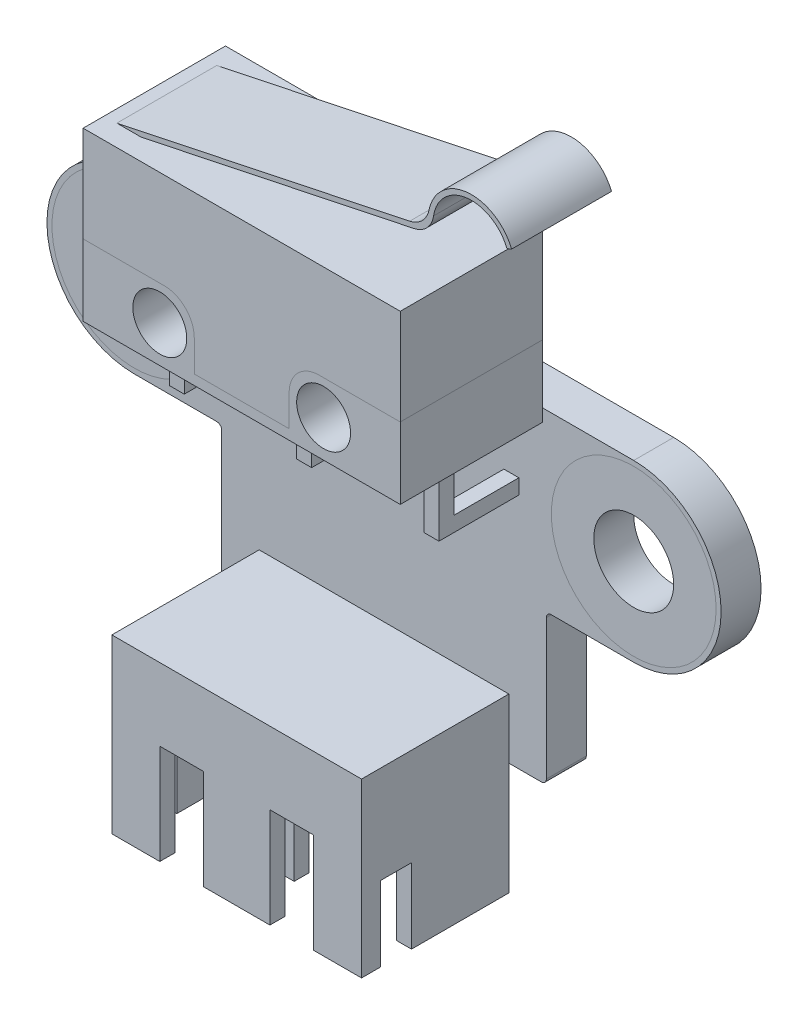
SolidWorks part; units mm, degrees
ref_plane "Přední rovina" through (0, 0, 0) normal (0, 0, 1) x (1, 0, 0)
ref_plane "Horní rovina" through (0, 0, 0) normal (0, 1, 0) x (1, 0, 0)
ref_plane "Pravá rovina" through (0, 0, 0) normal (1, 0, 0) x (0, 0, -1)
sketch "Skica1" plane through (0, 0, 0) normal (0, 0, 1) x (1, 0, 0)
  line L0 (0, 0) -> (20, 0) construction
  line L1 (0, 3.5) -> (20, 3.5)
  line L2 (0, -3.5) -> (3.5, -3.5)
  line L3 (3.5, -3.5) -> (3.5, -9.5)
  line L4 (3.5, -9.5) -> (16.5, -9.5)
  line L5 (16.5, -9.5) -> (16.5, -3.5)
  line L6 (16.5, -3.5) -> (20, -3.5)
  arc A0 (0, 3.5) -> (0, -3.5) centre (0, 0) ccw
  arc A1 (20, -3.5) -> (20, 3.5) centre (20, 0) ccw
  circle A2 centre (0, 0) radius 1.6
  circle A3 centre (20, 0) radius 1.6
  point P2 (0, 0)
  dimension "D1" = 27
  dimension "D5" = 3.2
  dimension "D6" = 3.2
  dimension "D2" = 13
  dimension "D3" = 13
  dimension "D4" = 20
extrude "Přidat vysunutím1" add sketch "Skica1" along normal blind 1.6
sketch "Skica2" plane through (0, 0, 1.6) normal (0, 0, 1) x (1, 0, 0)
  line L0 (20, 3.5) -> (0, 3.5) construction
  line L1 (3.65, 9.7) -> (16.35, 9.7)
  line L2 (3.65, 9.7) -> (3.65, 3)
  line L3 (3.65, 3) -> (16.35, 3)
  line L4 (16.35, 9.7) -> (16.35, 3)
  line L5 (3.65, 9.7) -> (16.35, 3) construction
  line L6 (3.65, 3) -> (16.35, 9.7) construction
  line L7 (10, 6.35) -> (10, -9.5) construction
  line L8 (3.5, -9.5) -> (16.5, -9.5) construction
  point P0 (10, 6.35)
  dimension "D1" = 6.2
  dimension "D2" = 12.7
  dimension "D3" = 6.7
extrude "Přidat vysunutím2" add sketch "Skica2" along normal blind 5.7
sketch "Skica3" plane through (0, 0, 1.6) normal (0, 0, 1) x (1, 0, 0)
  line L0 (3.5, -9.5) -> (16.5, -9.5) construction
  line L1 (5, -7.1) -> (15, -7.1)
  line L2 (5, -7.1) -> (5, -14)
  line L3 (5, -14) -> (15, -14)
  line L4 (15, -7.1) -> (15, -14)
  line L5 (5, -7.1) -> (15, -14) construction
  line L6 (5, -14) -> (15, -7.1) construction
  line L7 (10, -9.5) -> (10, -10.55) construction
  point P0 (10, -10.55)
  dimension "D1" = 10
  dimension "D2" = 6.9
  dimension "D3" = 4.5
extrude "Přidat vysunutím3" add sketch "Skica3" along normal blind 5.9
sketch "Skica4" plane through (0, -14, 0) normal (0, -1, 0) x (1, 0, 0)
  line L0 (5, 7.5) -> (15, 7.5) construction
  line L1 (5.6, 6.9) -> (14.4, 6.9)
  line L2 (5.6, 6.9) -> (5.6, 2.2)
  line L3 (5.6, 2.2) -> (14.4, 2.2)
  line L4 (14.4, 6.9) -> (14.4, 2.2)
  line L5 (15, 7.5) -> (15, 1.6) construction
  line L6 (5, 7.5) -> (5, 1.6) construction
  line L7 (5, 1.6) -> (15, 1.6) construction
  line L8 (9.7, 5.5) -> (10.3, 5.5)
  line L9 (7.16, 5.5) -> (7.76, 5.5)
  line L10 (7.16, 5.5) -> (7.16, 4.9)
  line L11 (7.16, 4.9) -> (7.76, 4.9)
  line L12 (7.76, 5.5) -> (7.76, 4.9)
  line L13 (7.16, 5.5) -> (7.76, 4.9) construction
  line L14 (7.16, 4.9) -> (7.76, 5.5) construction
  line L15 (9.7, 4.9) -> (10.3, 4.9)
  line L16 (10.3, 5.5) -> (10.3, 4.9)
  line L17 (9.7, 5.5) -> (9.7, 4.9)
  line L18 (12.24, 5.5) -> (12.84, 5.5)
  line L19 (12.24, 4.9) -> (12.84, 4.9)
  line L20 (12.84, 5.5) -> (12.84, 4.9)
  line L21 (12.24, 5.5) -> (12.24, 4.9)
  line L22 (10, 4.9) -> (10, 2.2) construction
  point P12 (7.46, 5.2)
  dimension "D1" = 0.6
  dimension "D2" = 0.6
  dimension "D3" = 0.6
  dimension "D4" = 0.6
  dimension "D5" = 0.6
  dimension "D7" = 2.54
  dimension "D8" = 3.9
  dimension "D6" = 3
extrude "Odebrat vysunutím1" cut sketch "Skica4" against normal blind 5.4
sketch "Skica5" plane through (15, 0, 0) normal (1, 0, 0) x (0, 0, -1)
  line L0 (-7.5, -14) -> (-7.5, -7.1) construction
  line L1 (-5.5, -14) -> (-6.75, -14)
  line L2 (-5.5, -14) -> (-5.5, -11)
  line L3 (-5.5, -11) -> (-6.75, -11)
  line L4 (-6.75, -14) -> (-6.75, -11)
  dimension "D1" = 0.75
  dimension "D2" = 3
extrude "Odebrat vysunutím2" cut sketch "Skica5" against normal blind 11.4
sketch "Skica6" plane through (0, 0, 7.5) normal (0, 0, 1) x (1, 0, 0)
  line L0 (5, -14) -> (15, -14) construction
  line L1 (13.08, -14) -> (11.33, -14)
  line L2 (13.08, -14) -> (13.08, -10)
  line L3 (13.08, -10) -> (11.33, -10)
  line L4 (11.33, -14) -> (11.33, -10)
  line L5 (15, -14) -> (15, -7.1) construction
  line L6 (10, -14) -> (10, -7.1) construction
  line L8 (15, -7.1) -> (5, -7.1) construction
  line L9 (8.67, -14) -> (8.67, -10)
  line L10 (6.92, -10) -> (8.67, -10)
  line L11 (6.92, -14) -> (6.92, -10)
  line L12 (6.92, -14) -> (8.67, -14)
  dimension "D1" = 1.92
  dimension "D2" = 1.75
  dimension "D3" = 4
extrude "Odebrat vysunutím3" cut sketch "Skica6" against normal blind 1
sketch "Skica7" plane through (0, 0, 1.6) normal (0, 0, 1) x (1, 0, 0)
  circle A0 centre (0, 0) radius 3.3
  arc A1 (0, 3.5) -> (0, -3.5) centre (0, 0) ccw construction
  circle A2 centre (20, 0) radius 3.3
  arc A3 (20, -3.5) -> (20, 3.5) centre (20, 0) ccw construction
  dimension "D1" = 0.2
  dimension "D2" = 0.2
split line "Rozdělovací křivka1"
fillet "Zaoblit1" radius 0.2 4 edges at (3.5, -9.5, 0.8) (16.5, -9.5, 0.8) (16.5, -3.5, 0.8) (3.5, -3.5, 0.8)
sketch "Skica8" plane through (0, -2.8, 7.3) normal (0, 0, -1) x (1, 0, 0)
  line L1 (6.72, -7.28) -> (13.28, -7.28) construction
  line L2 (13.28, -7.28) -> (10, -12.5) construction
  line L3 (16.35, -12.5) -> (3.65, -12.5) construction
  line L4 (10, -12.5) -> (6.72, -7.28) construction
  line L5 (3.65, -5.8) -> (16.35, -5.8) construction
  circle A0 centre (6.72, -7.28) radius 1.08
  circle A1 centre (13.28, -7.28) radius 1.08
  dimension "D1" = 4.4
  dimension "D2" = 8.72
  dimension "D3" = 1.48
extrude "Odebrat vysunutím4" cut sketch "Skica8" along normal up to surface (5.7 mm away) up to face at (3.3, 0, 1.6)
sketch "Skica9" plane through (0, 0, 7.3) normal (0, 0, 1) x (1, 0, 0)
  line L0 (3.65, 5.86) -> (6.9, 5.86)
  line L1 (3.65, 9.7) -> (3.65, 3) construction
  line L2 (8.1, 4.66) -> (8.1, 3.4)
  line L3 (8.1, 3.4) -> (11.9, 3.4)
  line L4 (11.9, 3.4) -> (11.9, 4.66)
  line L5 (13.1, 5.86) -> (16.35, 5.86)
  line L6 (16.35, 3) -> (16.35, 9.7) construction
  line L7 (3.65, 3) -> (16.35, 3) construction
  circle A1 centre (6.72, 4.48) radius 1.08 construction
  circle A3 centre (13.28, 4.48) radius 1.08 construction
  arc A4 (11.9, 4.66) -> (13.1, 5.86) centre (13.1, 4.66) cw
  arc A5 (8.1, 4.66) -> (6.9, 5.86) centre (6.9, 4.66) ccw
  dimension "D5" = 1.2
  dimension "D1" = 0.3
  dimension "D2" = 0.3
  dimension "D3" = 0.3
  dimension "D4" = 0.4
ref_plane "Rovina1" through (0, 0, 4.45) normal (0, 0, 1) x (1, 0, 0)
split line "Rozdělovací křivka2"
sketch "Skica11" plane through (16.35, 0, 0) normal (1, 0, 0) x (0, 0, -1)
  line L0 (-7.3, 5.86) -> (-1.6, 5.86)
  line L1 (-1.6, 3.5) -> (-1.6, 9.7) construction
split line "Rozdělovací křivka3"
sketch "Skica12" plane through (0, 0, 1.6) normal (0, 0, -1) x (-1, 0, 0)
  line L0 (-6.9, 5.86) -> (-3.65, 5.86) construction
  line L1 (-11.9, 4.66) -> (-11.9, 3.4) construction
  line L2 (-8.1, 3.4) -> (-8.1, 4.66) construction
  line L3 (-11.9, 3.4) -> (-8.1, 3.4) construction
  line L4 (-16.35, 5.86) -> (-13.1, 5.86) construction
  line L5 (-6.9, 5.86) -> (-3.65, 5.86)
  line L6 (-11.9, 4.66) -> (-11.9, 3.4)
  line L7 (-8.1, 3.4) -> (-8.1, 4.66)
  line L8 (-11.9, 3.4) -> (-8.1, 3.4)
  line L9 (-16.35, 5.86) -> (-13.1, 5.86)
  arc A0 (-6.9, 5.86) -> (-8.1, 4.66) centre (-6.9, 4.66) ccw construction
  arc A1 (-11.9, 4.66) -> (-13.1, 5.86) centre (-13.1, 4.66) ccw construction
  arc A2 (-6.9, 5.86) -> (-8.1, 4.66) centre (-6.9, 4.66) ccw
  arc A3 (-11.9, 4.66) -> (-13.1, 5.86) centre (-13.1, 4.66) ccw
split line "Rozdělovací křivka4"
ref_plane "Rovina2" through (0, 0, 4.45) normal (0, 0, 1) x (1, 0, 0)
sketch "Skica14" plane through (3.65, 0, 0) normal (-1, 0, 0) x (0, 0, 1)
  line L0 (1.6, 5.86) -> (7.3, 5.86)
split line "Rozdělovací křivka5"
sketch "Skica15" plane through (0, 0, 4.45) normal (0, 0, 1) x (1, 0, 0)
  line L0 (4.15, 9.7) -> (15.8776, 12.1628)
  line L1 (16.35, 9.7) -> (3.65, 9.7) construction
  line L2 (3.65, 9.7) -> (3.65, 5.86) construction
  line L3 (4.15, 9.7) -> (5.1231, 9.7)
  line L4 (5.1231, 9.7) -> (16.0506, 11.9948)
  line L5 (16.35, 9.7) -> (16.35, 16.7874) construction
  line L6 (19.7738, 13.1612) -> (19.9595, 13.2357)
  line L7 (16.35, 5.86) -> (16.35, 9.7) construction
  circle A0 centre (4.15, 9.7) radius 16.2 construction
  arc A1 (19.9595, 13.2357) -> (16.6515, 12.9398) centre (18.35, 12.59) ccw
  arc A2 (19.7738, 13.1612) -> (16.8335, 12.8221) centre (18.35, 12.59) ccw
  arc A3 (16.8335, 12.8221) -> (16.0506, 11.9948) centre (15.845, 12.9735) cw
  arc A4 (16.6515, 12.9398) -> (15.8776, 12.1628) centre (15.672, 13.1415) cw
  dimension "D4" = 32.4
  dimension "D5" = 0.2
  dimension "D6" = 0.2
  dimension "1" = 1
  dimension "D1" = 0.5
  dimension "D2" = 0.2
  dimension "D3" = 11.86
  dimension "D7" = 2
  dimension "D8" = 2.89
  dimension "D9" = 190
extrude "Přidat vysunutím4" add sketch "Skica15" along normal mid plane 4 contours L0 A4 A1 L6 A2 A3 L4 L3
ref_plane "Rovina3" through (0, 0, 4.8) normal (0, 0, 1) x (1, 0, 0)
sketch "Skica16" plane through (0, 0, 4.8) normal (0, 0, 1) x (1, 0, 0)
  line L0 (3.65, 3) -> (16.35, 3) construction
  line L1 (5.2, 3) -> (4.6, 3)
  line L2 (5.2, 3) -> (5.2, 0)
  line L3 (5.2, 0) -> (4.6, 0)
  line L4 (4.6, 3) -> (4.6, 0)
  line L5 (10, 3) -> (10, 9.7) construction
  line L6 (9.7, 3) -> (10.3, 3)
  line L7 (9.7, 3) -> (9.7, 0)
  line L8 (9.7, 0) -> (10.3, 0)
  line L9 (10.3, 3) -> (10.3, 0)
  line L10 (14.8, 3) -> (15.4, 3)
  line L11 (14.8, 3) -> (14.8, 0)
  line L12 (14.8, 0) -> (15.4, 0)
  line L13 (15.4, 3) -> (15.4, 0)
  line L14 (16.35, 9.7) -> (3.65, 9.7) construction
  point P14 (4.9, 0)
  point P15 (10, 0)
  point P16 (15.1, 0)
  dimension "D1" = 3
  dimension "D2" = 5.1
  dimension "D3" = 5.1
  dimension "D4" = 0.6
extrude "Přidat vysunutím5" add sketch "Skica16" against normal up to surface (3.2 mm away) up to face at (3.3, 0, 1.6)
sketch "Skica17" plane through (15.4, 0, 0) normal (1, 0, 0) x (0, 0, -1)
  line L0 (-4.8, 0) -> (-4.8, 3) construction
  line L1 (-1.6, 3) -> (-4.2, 3)
  line L2 (-1.6, 3) -> (-1.6, 0.6)
  line L3 (-1.6, 0.6) -> (-4.2, 0.6)
  line L4 (-4.2, 3) -> (-4.2, 0.6)
  line L5 (-1.6, 0) -> (-4.8, 0) construction
  dimension "D1" = 0.6
  dimension "D2" = 0.6
extrude "Odebrat vysunutím6" cut sketch "Skica17" against normal blind 12
